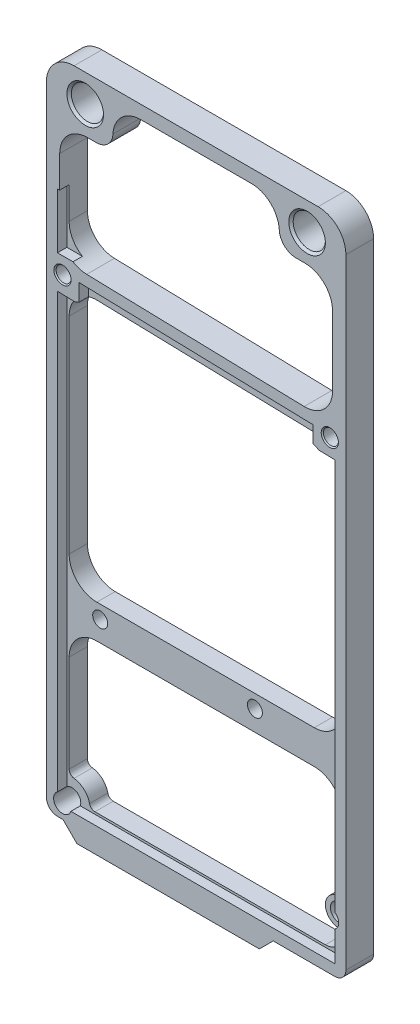
SolidWorks part; units mm, degrees
ref_plane "Front" through (0, 0, 0) normal (0, 0, 1) x (1, 0, 0)
ref_plane "Top" through (0, 0, 0) normal (0, 1, 0) x (1, 0, 0)
ref_plane "Right" through (0, 0, 0) normal (1, 0, 0) x (0, 0, -1)
sketch "Sketch1" plane through (0, 0, 0) normal (0, 0, 1) x (1, 0, 0)
  line L0 (0, 78.4) -> (54, 78.4) construction
  line L2 (0, 0) -> (0, 83.4)
  line L3 (5, 88.4) -> (49, 88.4)
  line L4 (54, 0) -> (54, 83.4)
  line L5 (27, 8.5492) -> (27, -24.6289) construction
  line L8 (0, 0) -> (0, -32.8)
  line L9 (0, -32.8) -> (54, -32.8)
  line L10 (54, 0) -> (54, -32.8)
  circle A0 centre (7, 83.4) radius 2.9
  circle A1 centre (47, 83.4) radius 2.9
  arc A2 (49, 88.4) -> (54, 83.4) centre (49, 83.4) cw
  arc A3 (5, 88.4) -> (0, 83.4) centre (5, 83.4) ccw
  circle A4 centre (2.9, 54.7) radius 1.35
  circle A5 centre (51.1, 53.4) radius 1.35
  circle A6 centre (8, 2.6) radius 1.35
  circle A7 centre (35.9, 2.6) radius 1.35
  circle A8 centre (2.9, -27.8) radius 1.6
  circle A9 centre (51.1, -21.6) radius 1.6
  dimension "D1" = 5.8
  dimension "D6" = 5
  dimension "D8" = 2.7
  dimension "D10" = 5.1
  dimension "D12" = 50.8
  dimension "D13" = 15.2
  dimension "D14" = 24.1
  dimension "D16" = 25
  dimension "D17" = 2.6
  dimension "D18" = 3.2
  dimension "D19" = 3.2
  dimension "D2" = 40
  dimension "D3" = 7
  dimension "D4" = 5
  dimension "D5" = 7
  dimension "D7" = 10
  dimension "D9" = 27.9
  dimension "D11" = 1.3
  dimension "D15" = 27
  dimension "D20" = 75
  dimension "D21" = 82.5
  dimension "D22" = 5
extrude "Boss-Extrude1" add sketch "Sketch1" along normal blind 5
sketch "Sketch2" plane through (0, 0, 5) normal (0, 0, 1) x (1, 0, 0)
  line L0 (5.5, -32.8) -> (3, -30.3)
  line L1 (0, -32.8) -> (54, -32.8) construction
  line L2 (3, -30.3) -> (0, -30.3)
  line L3 (0, 83.4) -> (0, -32.8) construction
  line L4 (0, -30.3) -> (0, -32.8)
  line L5 (0, -32.8) -> (5.5, -32.8)
  line L6 (38.4, -32.8) -> (40.9, -30.3)
  line L7 (40.9, -30.3) -> (54, -30.3)
  line L8 (54, -32.8) -> (54, 83.4) construction
  line L9 (54, -30.3) -> (54, -32.8)
  line L10 (54, -32.8) -> (38.4, -32.8)
  circle A0 centre (8, 2.6) radius 1.35 construction
  circle A1 centre (35.9, 2.6) radius 1.35 construction
  dimension "D3" = 5
  dimension "D1" = 2.5
  dimension "D2" = 45
  dimension "D4" = 5
extrude "Cut-Extrude1" cut sketch "Sketch2" against normal blind 5
sketch "Sketch3" plane through (0, 0, 5) normal (0, 0, 1) x (1, 0, 0)
  line L0 (12, 81) -> (12, 78.4)
  line L1 (12, 78.4) -> (7.4, 78.4)
  line L2 (2.4, 73.4) -> (2.4, 61.9696)
  line L3 (7.2679, 56.9714) -> (46.4679, 55.9356)
  line L4 (51.6, 60.9339) -> (51.6, 73.4)
  line L5 (46.6, 78.4) -> (42, 78.4)
  line L6 (42, 78.4) -> (42, 81)
  line L7 (37, 86) -> (17, 86)
  line L8 (49, 88.4) -> (5, 88.4) construction
  line L9 (54, -30.3) -> (54, 83.4) construction
  line L10 (0, 83.4) -> (0, -30.3) construction
  line L11 (7.5321, 52.1644) -> (46.7321, 51.1286)
  line L12 (51.6, 46.1304) -> (51.6, 10)
  line L13 (46.6, 5) -> (7.4, 5)
  line L14 (2.4, 10) -> (2.4, 47.1661)
  line L15 (0, 83.4) -> (0, -30.3) construction
  line L16 (7.4, -1.0766) -> (46.6, -1.0766)
  line L17 (2.4, -6.0766) -> (2.4, -24.5887)
  line L20 (54, -30.3) -> (54, 83.4) construction
  line L22 (54, -30.3) -> (40.9, -30.3) construction
  line L25 (6.1485, -27.9) -> (48.6, -27.9)
  line L27 (51.6, -19.1505) -> (51.6, -6.0766)
  line L28 (51.6, -24.0495) -> (51.6, -24.9)
  circle A0 centre (7, 83.4) radius 2.9 construction
  circle A1 centre (47, 83.4) radius 2.9 construction
  arc A2 (2.4, -6.0766) -> (7.4, -1.0766) centre (7.4, -6.0766) cw
  circle A3 centre (2.9, 54.7) radius 1.35 construction
  circle A4 centre (51.1, 53.4) radius 1.35 construction
  circle A5 centre (8, 2.6) radius 1.35 construction
  arc A6 (51.6, 10) -> (46.6, 5) centre (46.6, 10) cw
  arc A7 (7.4, 5) -> (2.4, 10) centre (7.4, 10) cw
  arc A8 (2.4, 47.1661) -> (7.5321, 52.1644) centre (7.4, 47.1661) cw
  arc A9 (51.6, 46.1304) -> (46.7321, 51.1286) centre (46.6, 46.1304) ccw
  arc A10 (51.6, 60.9339) -> (46.4679, 55.9356) centre (46.6, 60.9339) cw
  arc A11 (2.4, 61.9696) -> (7.2679, 56.9714) centre (7.4, 61.9696) ccw
  arc A12 (2.4, 73.4) -> (7.4, 78.4) centre (7.4, 73.4) cw
  arc A13 (51.6, 73.4) -> (46.6, 78.4) centre (46.6, 73.4) ccw
  arc A14 (42, 81) -> (37, 86) centre (37, 81) ccw
  arc A15 (12, 81) -> (17, 86) centre (17, 81) cw
  arc A16 (46.6, -1.0766) -> (51.6, -6.0766) centre (46.6, -6.0766) cw
  arc A17 (51.6, -19.1505) -> (51.6, -24.0495) centre (51.1, -21.6) ccw
  arc A18 (6.1485, -27.9) -> (2.4, -24.5887) centre (2.9, -27.8) ccw
  arc A19 (48.6, -27.9) -> (51.6, -24.9) centre (48.6, -24.9) ccw
  point P34 (2.4, 52.3)
  point P37 (51.6, 51)
  point P40 (51.6, 55.8)
  point P43 (2.4, 57.1)
  point P53 (0, 0)
  point P54 (50.6974, -1.0766)
  point P72 (51.3544, -20.78)
  dimension "D3" = 5
  dimension "D7" = 2.4
  dimension "D13" = 2.4
  dimension "D14" = 5
  dimension "D15" = 6.0766
  dimension "D21" = 5
  dimension "D22" = 6.5
  dimension "D18" = 5
  dimension "D19" = 5
  dimension "D23" = 3
  dimension "D1" = 5
  dimension "D2" = 5
  dimension "D4" = 2.4
  dimension "D5" = 2.4
  dimension "D6" = 2.4
  dimension "D8" = 2.4
  dimension "D9" = 2.4
  dimension "D10" = 2.4
  dimension "D11" = 2.4
  dimension "D12" = 2.4
  dimension "D16" = 2.4
  dimension "D17" = 2.4
  dimension "D20" = 2.4
extrude "Cut-Extrude2" cut sketch "Sketch3" against normal blind 5
chamfer "Chamfer1" distance 0.4 angle 45 4 edges at (49.9, 83.4, 0) (49.9, 83.4, 5) (9.9, 83.4, 0) (9.9, 83.4, 5)
chamfer "Chamfer2" distance 0.2 angle 45 8 edges at (37.25, 2.6, 0) (37.25, 2.6, 5) (9.35, 2.6, 0) (9.35, 2.6, 5) (52.45, 53.4, 0) (52.45, 53.4, 5) (4.25, 54.7, 0) (4.25, 54.7, 5)
fillet "Fillet1" radius 3 2 edges at (42, 78.4, 2.5) (12, 78.4, 2.5)
fillet "Fillet2" radius 2 2 edges at (54, -30.3, 2.5) (0, -30.3, 2.5)
fillet "Fillet3" radius 1 4 edges at (51.6, -24.0495, 2.5) (51.6, -19.1505, 2.5) (6.1485, -27.9, 2.5) (2.4, -24.5887, 2.5)
sketch "Sketch4" plane through (0, 0, 5) normal (0, 0, 1) x (1, 0, 0)
  line L0 (46.6, -1.0766) -> (7.4, -1.0766) construction
  line L5 (7.4, 5) -> (46.6, 5) construction
  line L6 (11.5, 5) -> (32.4, 5)
  line L7 (11.5, 5) -> (11.5, -1.0766)
  line L8 (11.5, -1.0766) -> (32.4, -1.0766)
  line L9 (32.4, 5) -> (32.4, -1.0766)
  circle A0 centre (8, 2.6) radius 1.35 construction
  circle A1 centre (35.9, 2.6) radius 1.35 construction
  dimension "D1" = 3.5
  dimension "D2" = 3.5
extrude "Cut-Extrude3" cut sketch "Sketch4" against normal blind 1.7
sketch "Sketch5" plane through (0, 0, 5) normal (0, 0, 1) x (1, 0, 0)
  line L0 (0, 83.4) -> (0, -28.3) construction
  line L1 (2, 51.6963) -> (52, 50.3752)
  line L2 (2, 51.6963) -> (2, -28.3)
  line L3 (2, -28.3) -> (52, -28.3)
  line L4 (52, 50.3752) -> (52, -28.3)
  line L5 (54, -28.3) -> (54, 83.4) construction
  line L8 (2.4, 73.4) -> (2.4, 61.9696) construction
  line L9 (2, 57.7) -> (10, 57.7)
  line L10 (2, 57.7) -> (2, 67.6848)
  line L11 (2, 67.6848) -> (10, 67.6848)
  line L12 (10, 57.7) -> (10, 67.6848)
  line L13 (46.7321, 51.1286) -> (7.5321, 52.1644) construction
  line L14 (52, -30.3) -> (40.9, -30.3) construction
  circle A0 centre (2.9, 54.7) radius 1.35 construction
  circle A4 centre (51.1, 53.4) radius 1.35 construction
  point P20 (2.4, 67.6848)
  dimension "D6" = 3
  dimension "D1" = 2
  dimension "D2" = 2
  dimension "D3" = 2
  dimension "D4" = 2
  dimension "D5" = 8
  dimension "D7" = 3
extrude "Cut-Extrude5" cut sketch "Sketch5" against normal blind 1.7
sketch "Sketch6" plane through (0, 0, 5) normal (0, 0, 1) x (1, 0, 0)
  line L0 (48.1, 53.8918) -> (5.9, 55.0068)
  line L1 (5.9, 55.0068) -> (5.9, 50.5538)
  line L2 (5.9, 50.5538) -> (48.1, 49.4388)
  line L3 (48.1, 49.4388) -> (48.1, 53.8918)
  line L4 (46.7321, 51.1286) -> (7.5321, 52.1644) construction
  line L5 (7.2679, 56.9714) -> (46.4679, 55.9356) construction
  circle A0 centre (51.1, 53.4) radius 1.35 construction
  circle A1 centre (2.9, 54.7) radius 1.35 construction
  dimension "D1" = 3
  dimension "D2" = 3
  dimension "D3" = 2
extrude "Cut-Extrude6" cut sketch "Sketch6" against normal up to surface (1.7 mm away) up to face at (29.1504, -17.7111, 3.3)
